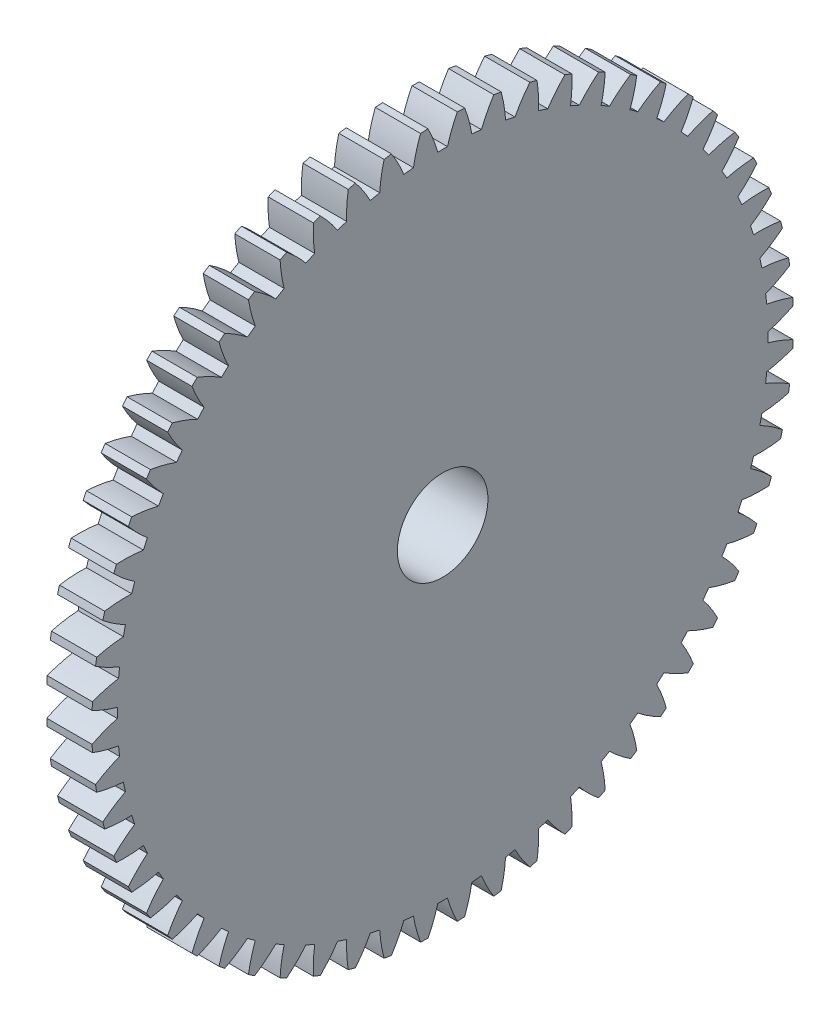
SolidWorks part; units mm, degrees
material "ABS"
ref_plane "Plane1" through (0, 0, 0) normal (0, 0, 1) x (1, 0, 0)
ref_plane "Plane2" through (0, 0, 0) normal (0, 1, 0) x (1, 0, 0)
ref_plane "Plane3" through (0, 0, 0) normal (1, 0, 0) x (0, 0, -1)
sketch "HoldingSke" plane through (0, 0, 0) normal (0, 1, 0) x (1, 0, 0)
  line L0 (0, 0) -> (203.2, -351.9527)
  line L1 (-15, 0) -> (100, 0) construction
  line L2 (0, 0) -> (-2.1039, 2.3779)
  line L3 (0, 0) -> (-11.863, 4.5341)
  line L4 (0, 0) -> (4.318, 7.479)
  line L5 (0, 0) -> (-23.7986, -8.8762)
  line L6 (0, 0) -> (-5.2639, -3.5516)
  line L7 (-2.1039, 2.3779) -> (3.3635, 27.1825)
  line L8 (-76.2, 54.61) -> (-61.976, 54.61)
  line L9 (-71.009, 38.7566) -> (-53.1078, 45.2721)
  line L10 (-76.2, 71.12) -> (104.1128, 71.12)
  line L11 (0, 0) -> (-6.35, 0)
  line L12 (-76.2, 101.6) -> (-76.1428, 101.6)
  line L13 (24.9733, 27.94) -> (52.9518, 28.4284)
  line L14 (24.9733, 27.94) -> (24.9746, 27.94)
  line L15 (24.9733, 27.94) -> (100.4006, 29.5858)
  circle A0 centre (0, 0) radius 6.35
  circle A1 centre (0, 0) radius 15.875
  circle A2 centre (0, 0) radius 15.875
  circle A3 centre (0, 0) radius 6.35
  dimension "MHD" = 31.75
  dimension "Hub_dia" = 31.75
  dimension "Bore" = 12.7
  dimension "MBD" = 12.7
  dimension "Num_teeth" = 60
  dimension "Pitch" = 406.4
  dimension "Overall_len" = 25.4
  dimension "Show_teeth" = 60
  dimension "Thickness" = 6.35
  dimension "OAL" = 25.4001
  dimension "T_dim" = 14.224
  dimension "Ap" = 20
  dimension "H" = 19.05
  dimension "Pitch_radius" = 180.3128
  dimension "Width" = 6.35
  dimension "Backlash" = 0.0571
  dimension "Addendum_fac" = 1
  dimension "Dedendum_fac" = 1.25
  dimension "Clearance_fac" = 0.25
  dimension "Dedendum_add" = 0.0013
sketch "BasProSke" plane through (0, 0, 0) normal (0, 1, 0) x (1, 0, 0)
  line L0 (-10, 0) -> (60, 0) construction
  line L1 (0, 0) -> (0, 49.2125)
  line L2 (0, 0) -> (6.35, 0)
  line L3 (6.35, 0) -> (6.35, 49.2125)
  line L4 (6.35, 49.2125) -> (0, 49.2125)
  dimension "Thickness" = 6.35
  dimension "Diameter" = 98.425
revolve "Base-Revolve" add sketch "BasProSke" angle 360 about L0
sketch "TooCutSke" plane through (0, 0, 0) normal (1, 0, 0) x (0, 0, -1)
  line L1 (0, 0) -> (0, 107) construction
  line L2 (0, 0) -> (-1.3467, 47.606) construction
  line L3 (0, 0) -> (-4.9836, 95.0919) construction
  line L4 (-1.3467, 47.606) -> (-2.4918, 47.5459) construction
  arc A0 (0.6776, 45.6343) -> (-0.6776, 45.6343) centre (0, 0) ccw
  arc A1 (2.0706, 49.1943) -> (-2.0706, 49.1943) centre (0, 0) ccw
  circle A2 centre (0, 0) radius 47.625 construction
  circle A3 centre (0, 0) radius 44.7529 construction
  arc A4 (-0.6776, 45.6343) -> (-2.0706, 49.1943) centre (-19.0248, 40.5077) ccw
  arc A5 (2.0706, 49.1943) -> (0.6776, 45.6343) centre (19.0248, 40.5077) ccw
  dimension "Root_dia" = 91.2787
  dimension "Overcut_dia" = 98.4758
  dimension "Pitch_dia" = 95.25
  dimension "Base_dia" = 89.5057
  dimension "Flank_rad" = 19.05
  dimension "Half_ang" = 3
  dimension "Half_CT" = 1.1467
extrude "ToothCut" cut sketch "TooCutSke" along normal through all
fillet "Breaks" [suppressed] radius 0.0318
fillet "RootFillets" [suppressed] radius 0.3981
pattern_circular "TeethCuts" count 60 every 6 about axis through (-10, 0, 0) along (1, 0, 0) of "ToothCut", "RootFillets", "Breaks"
sketch "HubNeaOneSke" plane through (0, 0, 0) normal (-1, 0, 0) x (0, 0, 1)
  circle A0 centre (0, 0) radius 15.875
  dimension "Diameter" = 31.75
extrude "HubNearOne" add sketch "HubNeaOneSke" along normal blind 19.0501
sketch "HubNeaBotSke" plane through (0, 0, 0) normal (-1, 0, 0) x (0, 0, 1)
  circle A0 centre (0, 0) radius 15.875
  dimension "Diameter" = 31.75
extrude "HubNearBoth" [suppressed] add sketch "HubNeaBotSke" along normal blind 9.525
ref_plane "FarPln" through (6.35, 0, 0) normal (1, 0, 0) x (0, 0, -1)
sketch "HubFarSke" plane through (6.35, 0, 0) normal (1, 0, 0) x (0, 0, -1)
  circle A0 centre (0, 0) radius 15.875
  dimension "Diameter" = 31.75
extrude "HubFar" [suppressed] add sketch "HubFarSke" along normal blind 9.525
sketch "BorSke" plane through (0, 0, 0) normal (1, 0, 0) x (0, 0, -1)
  circle A0 centre (0, 0) radius 6.35
  dimension "Diameter" = 12.7
extrude "Bore" cut sketch "BorSke" along normal mid plane 50.8001
sketch "KeySke" plane through (0, 0, 0) normal (1, 0, 0) x (0, 0, -1)
  line L0 (-1.5875, 0) -> (-1.5875, 7.874)
  line L1 (-1.5875, 7.874) -> (1.5875, 7.874)
  line L2 (1.5875, 7.874) -> (1.5875, 0)
  line L3 (0, 0) -> (0, 34) construction
  line L4 (-1.5875, 0) -> (1.5875, 0)
  dimension "Offset" = 7.874
  dimension "Width" = 3.175
extrude "Keyway" [suppressed] cut sketch "KeySke" along normal mid plane 50.8001
pattern_circular "Keyway2" [suppressed] count 2 every 90 about axis through (-10, 0, 0) along (1, 0, 0)
sketch "Sketch1" plane through (0, 0, 0) normal (0, 0, 1) x (1, 0, 0)
  line L0 (0, 0) -> (-19.0501, 0) construction
  line L1 (0, 15.875) -> (0, -15.875) construction
  line L2 (-19.0501, 15.875) -> (-19.0501, -15.875) construction
  circle A0 centre (-9.525, 0) radius 1.5875
  dimension "D1" = 3.175
extrude "Cut-Extrude1" cut sketch "Sketch1" against normal through all and the other way through all
fillet "Fillet1" radius 1.27 3 edges at (-19.0501, 0, 6.35) (-19.0501, 0, 15.875) (0, 0, -15.875)
equation "' \"Pitch@HoldingSke\" = 4"
equation "' \"Num_teeth@HoldingSke\" = 12"
equation "' \"Ap@HoldingSke\" =  20"
equation "' \"Ap@HoldingSke\" = 20"
equation "' \"Width@HoldingSke\" = 0.5"
equation "' \"Hub_dia@HoldingSke\"= 1"
equation "' \"Hub_dia@HoldingSke\" = 1"
equation "' \"Overall_len@HoldingSke\" = 1.0"
equation "' \"Bore@HoldingSke\" = 0.75"
equation "' \"T_dim@HoldingSke\" = 0.85"
equation "' \"Width@KeySke\" = 0.25"
equation "' \"Show_teeth@HoldingSke\" = 13"
equation "' \"Backlash@HoldingSke\" = 0.009"
equation "' \"Addendum_fac@HoldingSke\" = 1.0"
equation "' \"Dedendum_fac@HoldingSke\" = 1.25"
equation "' \"Dedendum_add@HoldingSke\" = 0.00005"
equation "' \"Clearance_fac@HoldingSke\" = 0.25"
equation "' \"Pitch@HoldingSke\" = 0.5"
equation "' \"Num_teeth@HoldingSke\" = 23"
equation "' \"Show_teeth@HoldingSke\" = 23"
equation "' \"Backlash@HoldingSke\" = 0.0375"
equation "\"Overcut_dia@TooCutSke\" = (\"Num_teeth@HoldingSke\" + 2 * \"Addendum_fac@HoldingSke\") / \"Pitch@HoldingSke\" + 0.002"
equation "\"Pitch_dia@TooCutSke\" = \"Num_teeth@HoldingSke\" / \"Pitch@HoldingSke\""
equation "\"Base_dia@TooCutSke\" = \"Num_teeth@HoldingSke\" / \"Pitch@HoldingSke\" * cos((\"Ap@HoldingSke\"  * 3.14159265 / 180))"
equation "\"Root_dia@TooCutSke\" = (\"Num_teeth@HoldingSke\" + 2) / \"Pitch@HoldingSke\" - 2 * (\"Addendum_fac@HoldingSke\" + \"Dedendum_fac@HoldingSke\") / \"Pitch@HoldingSke\" - \"Dedendum_add@HoldingSke\" * 2"
equation "\"Half_ang@TooCutSke\" = 180 / \"Num_teeth@HoldingSke\""
equation "\"Half_CT@TooCutSke\" = \"Num_teeth@HoldingSke\" / \"Pitch@HoldingSke\" * sin((3.14159265 / 2 / \"Num_teeth@HoldingSke\")) / 2 - 7 * \"Backlash@HoldingSke\" / 4"
equation "\"Flank_rad@TooCutSke\" = \"Num_teeth@HoldingSke\" / \"Pitch@HoldingSke\" / 5"
equation "\"Radius@RootFillets\" = \"Clearance_fac@HoldingSke\" / \"Pitch@HoldingSke\" + \"Dedendum_add@HoldingSke\""
equation "\"Break_rad@Breaks\" = 0.02 / \"Pitch@HoldingSke\""
equation "\"Thickness@HoldingSke\" = \"Width@HoldingSke\""
equation "\"OAL@HoldingSke\" = \"Thickness@HoldingSke\""
equation "\"MHD@HoldingSke\" = (\"Num_teeth@HoldingSke\" + 2) / \"Pitch@HoldingSke\" - 2 * (\"Addendum_fac@HoldingSke\" + \"Dedendum_fac@HoldingSke\")  / \"Pitch@HoldingSke\" - \"Dedendum_add@HoldingSke\" * 2"
equation "\"MBD@HoldingSke\" = (\"Num_teeth@HoldingSke\" + 2) / \"Pitch@HoldingSke\" - 2 * (\"Addendum_fac@HoldingSke\" + \"Dedendum_fac@HoldingSke\")  / \"Pitch@HoldingSke\" - \"Dedendum_add@HoldingSke\" * 2 - 0.002"
equation "\"MHD@HoldingSke\" = ((sgn( \"MHD@HoldingSke\" - \"Hub_dia@HoldingSke\" )-1)*( \"MHD@HoldingSke\" - \"Hub_dia@HoldingSke\" ))/-2+ \"Hub_dia@HoldingSke\""
equation "\"MBD@HoldingSke\" = ((sgn( \"MBD@HoldingSke\" - \"Bore@HoldingSke\" )-1)*( \"MBD@HoldingSke\" - \"Bore@HoldingSke\" ))/-2+ \"Bore@HoldingSke\""
equation "\"OAL@HoldingSke\" = ((sgn( \"OAL@HoldingSke\" - \"Overall_len@HoldingSke\" )+1)*( \"OAL@HoldingSke\" - \"Overall_len@HoldingSke\" ))/2 + \"Overall_len@HoldingSke\" + 0.000002"
equation "\"Num_teeth@TeethCuts\" = int( \"Show_teeth@HoldingSke\" ) + 1"
equation "\"Num_teeth@TeethCuts\" = ((sgn( \"Num_teeth@TeethCuts\" - \"Num_teeth@HoldingSke\" )-1)*( \"Num_teeth@TeethCuts\" - \"Num_teeth@HoldingSke\" ))/-2+ \"Num_teeth@HoldingSke\""
equation "\"Num_teeth@TeethCuts\" = ((sgn( \"Num_teeth@TeethCuts\" - 2.0)+1)*( \"Num_teeth@TeethCuts\" - 2.0))/2 +2.0"
equation "\"Angle@TeethCuts\" = 360.0 / \"Num_teeth@HoldingSke\""
equation "\"Diameter@BasProSke\" = (\"Num_teeth@HoldingSke\" + 2 * \"Addendum_fac@HoldingSke\") / \"Pitch@HoldingSke\""
equation "\"Thickness@BasProSke\"  = \"Thickness@HoldingSke\""
equation "' \"Fillet_rad@BasProSke\" =  \"Thickness@HoldingSke\" * 0.05"
equation "' \"Fillet_rad@BasProSke\" = \"Thickness@HoldingSke\" * 0.05"
equation "\"MHD@HoldingSke\" = ((sgn( \"MHD@HoldingSke\" - \"Root_dia@TooCutSke\" )-1)*( \"MHD@HoldingSke\" - \"Root_dia@TooCutSke\" ))/-2+ \"Root_dia@TooCutSke\""
equation "\"Diameter@HubNeaOneSke\" = \"MHD@HoldingSke\""
equation "\"Length@HubNearOne\" = \"OAL@HoldingSke\" - \"Thickness@BasProSke\""
equation "\"Diameter@HubNeaBotSke\" = \"MHD@HoldingSke\""
equation "\"Length@HubNearBoth\" = ( \"OAL@HoldingSke\" - \"Thickness@BasProSke\" ) / 2.0"
equation "\"Thickness@FarPln\" = \"Thickness@BasProSke\""
equation "\"Diameter@HubFarSke\" = \"MHD@HoldingSke\""
equation "\"Length@HubFar\" = ( \"OAL@HoldingSke\" - \"Thickness@BasProSke\" ) / 2.0"
equation "\"Diameter@BorSke\" = \"MBD@HoldingSke\""
equation "\"D1@Bore\" = \"OAL@HoldingSke\" * 2.0"
equation "\"D1@Keyway\" = \"OAL@HoldingSke\" * 2.0"
equation "\"Offset@KeySke\" = \"T_dim@HoldingSke\" - \"MBD@HoldingSke\" / 2.0"
